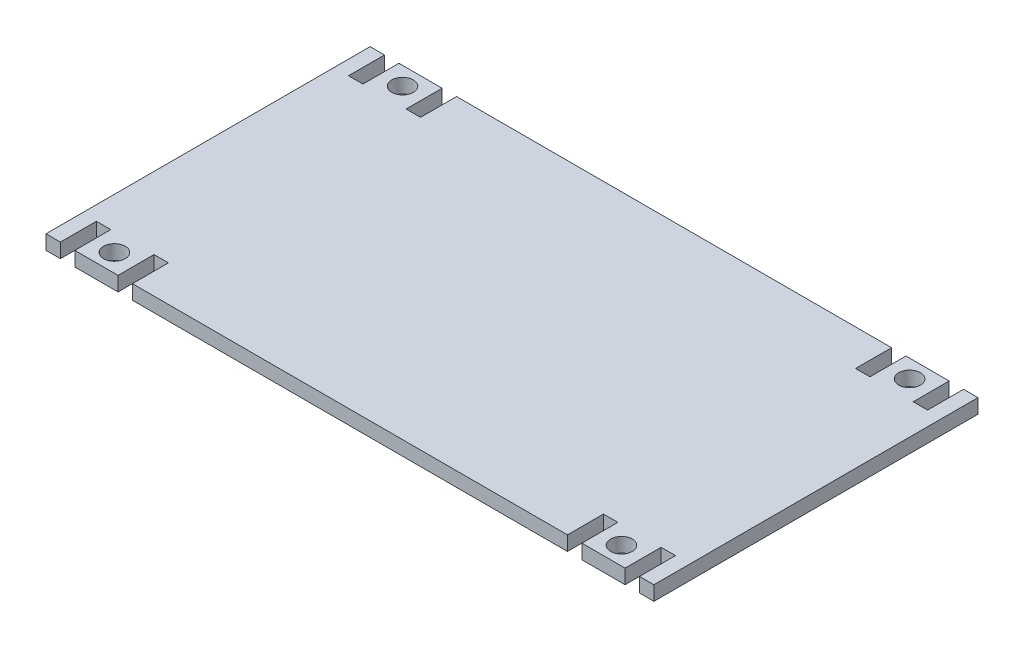
SolidWorks part; units mm, degrees
ref_plane "Front Plane" through (0, 0, 0) normal (0, 0, 1) x (1, 0, 0)
ref_plane "Top Plane" through (0, 0, 0) normal (0, 1, 0) x (1, 0, 0)
ref_plane "Right Plane" through (0, 0, 0) normal (1, 0, 0) x (0, 0, -1)
sketch "Sketch1" plane through (0, 0, 0) normal (0, 1, 0) x (1, 0, 0)
  line L0 (42.2, 45) -> (42.2, 0) construction
  line L1 (0, 0) -> (2, 0)
  line L2 (0, 0) -> (0, 45)
  line L3 (0, 45) -> (2, 45)
  line L4 (84.4, 0) -> (84.4, 45)
  line L5 (0, 22.5) -> (84.4, 22.5) construction
  line L6 (7, 45) -> (7, 42.5) construction
  line L7 (7, 42.5) -> (11, 42.5) construction
  line L9 (10, 40) -> (12, 40)
  line L10 (10, 40) -> (10, 45)
  line L12 (12, 40) -> (12, 45)
  line L13 (10, 40) -> (12, 45) construction
  line L14 (10, 45) -> (12, 40) construction
  line L15 (2, 40) -> (2, 45)
  line L16 (4, 40) -> (2, 40)
  line L17 (4, 40) -> (4, 45)
  line L19 (72.4, 40) -> (72.4, 45)
  line L20 (74.4, 40) -> (72.4, 40)
  line L21 (74.4, 40) -> (74.4, 45)
  line L22 (80.4, 40) -> (80.4, 45)
  line L23 (80.4, 40) -> (82.4, 40)
  line L24 (82.4, 40) -> (82.4, 45)
  line L27 (12, 5) -> (12, 0)
  line L28 (10, 5) -> (12, 5)
  line L29 (10, 5) -> (10, 0)
  line L30 (4, 5) -> (4, 0)
  line L31 (4, 5) -> (2, 5)
  line L32 (2, 5) -> (2, 0)
  line L35 (82.4, 5) -> (82.4, 0)
  line L36 (80.4, 5) -> (82.4, 5)
  line L37 (80.4, 5) -> (80.4, 0)
  line L38 (74.4, 5) -> (74.4, 0)
  line L39 (74.4, 5) -> (72.4, 5)
  line L40 (72.4, 5) -> (72.4, 0)
  line L42 (4, 0) -> (10, 0)
  line L43 (12, 0) -> (72.4, 0)
  line L44 (4, 45) -> (10, 45)
  line L45 (12, 45) -> (72.4, 45)
  line L46 (82.4, 45) -> (84.4, 45)
  line L47 (74.4, 45) -> (80.4, 45)
  line L48 (82.4, 0) -> (84.4, 0)
  line L49 (74.4, 0) -> (80.4, 0)
  circle A0 centre (7, 42.5) radius 1.5
  circle A1 centre (77.4, 42.5) radius 1.5
  circle A2 centre (7, 2.5) radius 1.5
  circle A3 centre (77.4, 2.5) radius 1.5
  dimension "D3" = 3
  dimension "D1" = 84.4
  dimension "D2" = 45
  dimension "D4" = 2
  dimension "D5" = 5
  dimension "D7" = 2
  dimension "D8" = 6
extrude "Boss-Extrude1" add sketch "Sketch1" along normal blind 2
